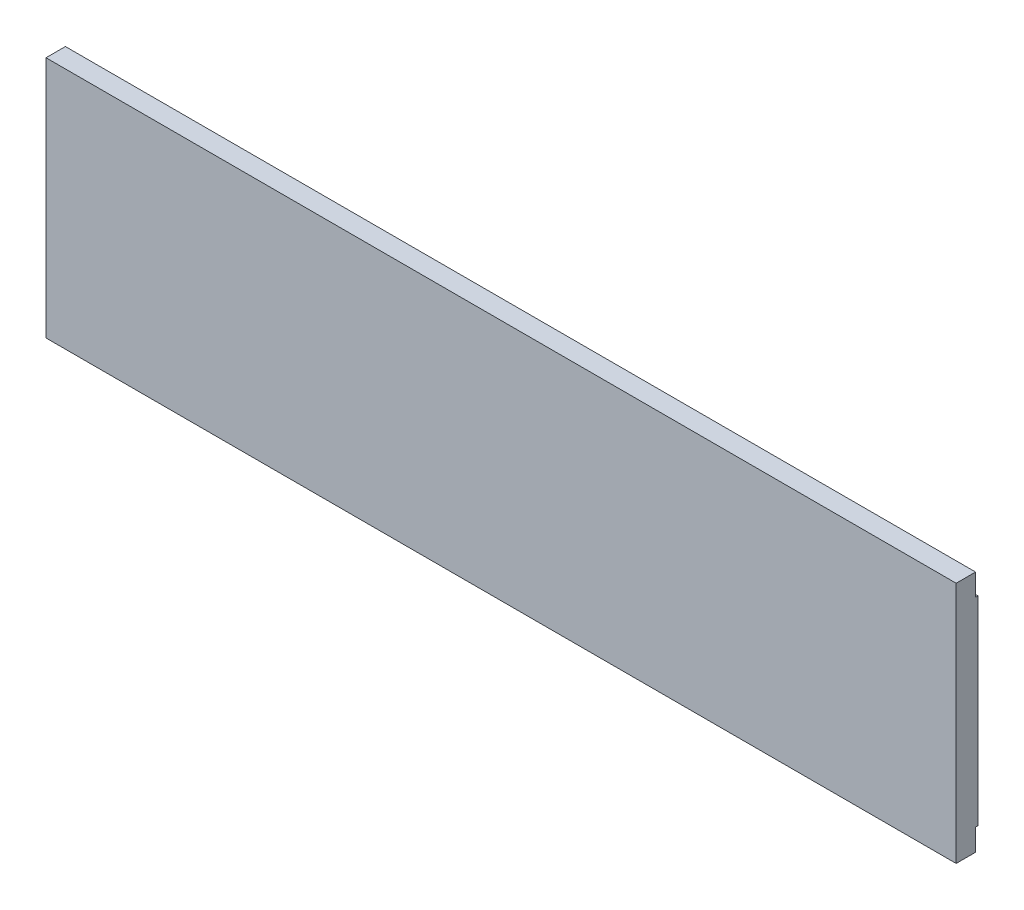
SolidWorks part; units mm, degrees
ref_plane "Front Plane" through (0, 0, 0) normal (0, 0, 1) x (1, 0, 0)
ref_plane "Top Plane" through (0, 0, 0) normal (0, 1, 0) x (1, 0, 0)
ref_plane "Right Plane" through (0, 0, 0) normal (1, 0, 0) x (0, 0, -1)
sketch "Sketch1" plane through (0, 0, 0) normal (0, 0, 1) x (1, 0, 0)
  line L1 (-375, 100) -> (375, 100)
  line L2 (-375, 100) -> (-375, -100)
  line L3 (-375, -100) -> (375, -100)
  line L4 (375, 100) -> (375, -100)
  line L5 (-375, 100) -> (375, -100) construction
  line L6 (-375, -100) -> (375, 100) construction
  point P0 (0, 0)
  dimension "D1" = 750
  dimension "D2" = 200
extrude "Boss-Extrude1" add sketch "Sketch1" along normal blind 18
sketch "Sketch2" plane through (-375, 0, 0) normal (-1, 0, 0) x (0, 0, 1)
  line L1 (0, -100) -> (2, -100)
  line L2 (0, -100) -> (0, -82)
  line L3 (0, -82) -> (2, -82)
  line L4 (2, -100) -> (2, -82)
  line L5 (0, 100) -> (2, 100)
  line L6 (0, 100) -> (0, 82)
  line L7 (0, 82) -> (2, 82)
  line L8 (2, 100) -> (2, 82)
  dimension "D1" = 18
  dimension "D2" = 2
  dimension "D3" = 2
  dimension "D4" = 18
extrude "Cut-Extrude3" cut sketch "Sketch2" against normal through all
sketch "Sketch3" plane through (0, 0, 0) normal (0, 0, -1) x (-1, 0, 0)
  line L0 (375, 82) -> (375, -82) construction
  line L1 (285, -136.9626) -> (267, -136.9626)
  line L2 (285, -136.9626) -> (285, 191.7955)
  line L3 (285, 191.7955) -> (267, 191.7955)
  line L4 (267, -136.9626) -> (267, 191.7955)
  line L5 (147, -160.7386) -> (129, -160.7386)
  line L6 (147, -160.7386) -> (147, 212.0905)
  line L7 (147, 212.0905) -> (129, 212.0905)
  line L8 (129, -160.7386) -> (129, 212.0905)
  line L9 (9, -149.114) -> (-9, -149.114)
  line L10 (9, -149.114) -> (9, 220.3889)
  line L11 (9, 220.3889) -> (-9, 220.3889)
  line L12 (-9, -149.114) -> (-9, 220.3889)
  line L13 (-129, -149.114) -> (-147, -149.114)
  line L14 (-129, -149.114) -> (-129, 234.8925)
  line L15 (-129, 234.8925) -> (-147, 234.8925)
  line L16 (-147, -149.114) -> (-147, 234.8925)
  line L17 (-267, -136.9626) -> (-285, -136.9626)
  line L18 (-267, -136.9626) -> (-267, 253.1818)
  line L19 (-267, 253.1818) -> (-285, 253.1818)
  line L20 (-285, -136.9626) -> (-285, 253.1818)
  dimension "D1" = 18
  dimension "D2" = 18
  dimension "D3" = 18
  dimension "D4" = 18
  dimension "D5" = 18
  dimension "D6" = 90
  dimension "D7" = 120
  dimension "D8" = 120
  dimension "D9" = 120
  dimension "D10" = 120
extrude "Cut-Extrude4" cut sketch "Sketch3" against normal blind 2
